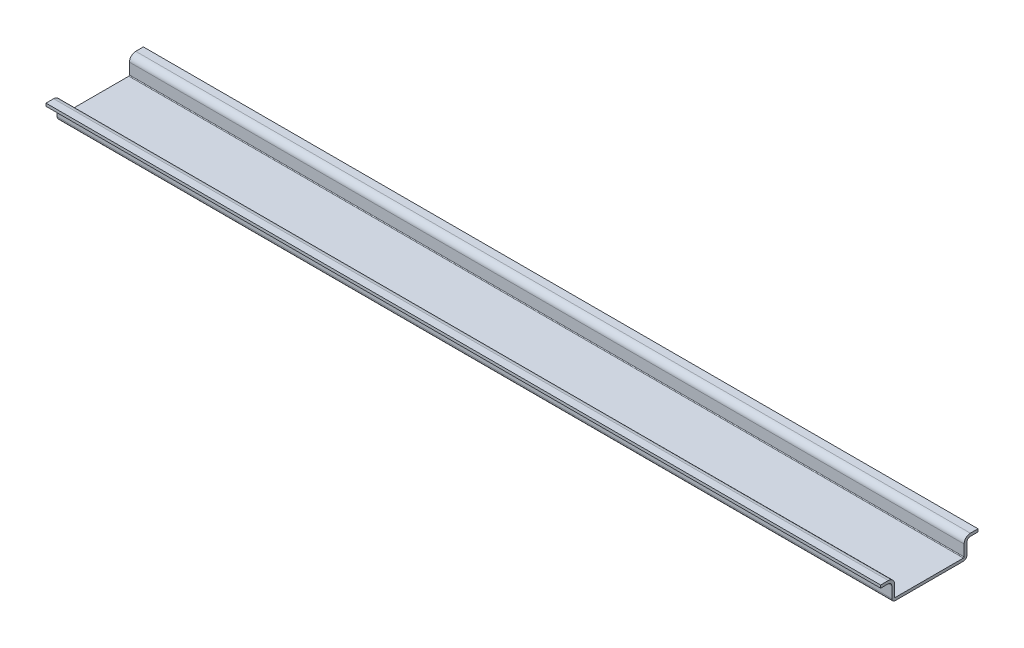
SolidWorks part; units mm, degrees
ref_plane "Front Plane" through (0, 0, 0) normal (0, 0, 1) x (1, 0, 0)
ref_plane "Top Plane" through (0, 0, 0) normal (0, 1, 0) x (1, 0, 0)
ref_plane "Right Plane" through (0, 0, 0) normal (1, 0, 0) x (0, 0, -1)
sketch3d "3DSketch1"
  line L0 (-150, 0, 0) -> (150, 0, 0)
  point P4 (0, 0, 0)
  dimension "D1" = 300
other "Omega TS-35(1)"
ref_plane "Plane1" through (-150, 0, 0) normal (1, 0, 0) x (0, 0, -1)
sketch "Sketch2" plane through (-150, 0, 0) normal (1, 0, 0) x (0, 0, -1)
  line L0 (12.25, 0) -> (-12.25, 0)
  line L1 (13.5, 1.25) -> (13.5, 5.25)
  line L2 (14.75, 6.5) -> (17.5, 6.5)
  line L3 (-14.75, 6.5) -> (-17.5, 6.5)
  line L4 (-13.5, 1.25) -> (-13.5, 5.25)
  line L5 (14.75, 7.5) -> (17.5, 7.5)
  line L6 (12.5, 1.25) -> (12.5, 5.25)
  line L7 (12.25, 1) -> (-12.25, 1)
  line L8 (-12.5, 1.25) -> (-12.5, 5.25)
  line L9 (-14.75, 7.5) -> (-17.5, 7.5)
  line L10 (17.5, 6.5) -> (17.5, 7.5)
  line L11 (-17.5, 6.5) -> (-17.5, 7.5)
  arc A0 (13.5, 5.25) -> (14.75, 6.5) centre (14.75, 5.25) cw
  arc A1 (-14.75, 6.5) -> (-13.5, 5.25) centre (-14.75, 5.25) cw
  arc A2 (-12.25, 0) -> (-13.5, 1.25) centre (-12.25, 1.25) cw
  arc A3 (12.25, 0) -> (13.5, 1.25) centre (12.25, 1.25) ccw
  arc A4 (12.5, 5.25) -> (14.75, 7.5) centre (14.75, 5.25) cw
  arc A5 (12.25, 1) -> (12.5, 1.25) centre (12.25, 1.25) ccw
  arc A6 (-12.25, 1) -> (-12.5, 1.25) centre (-12.25, 1.25) cw
  arc A7 (-14.75, 7.5) -> (-12.5, 5.25) centre (-14.75, 5.25) cw
  point P2 (0, 0)
  point P29 (0, 0)
  point P30 (0, 0)
